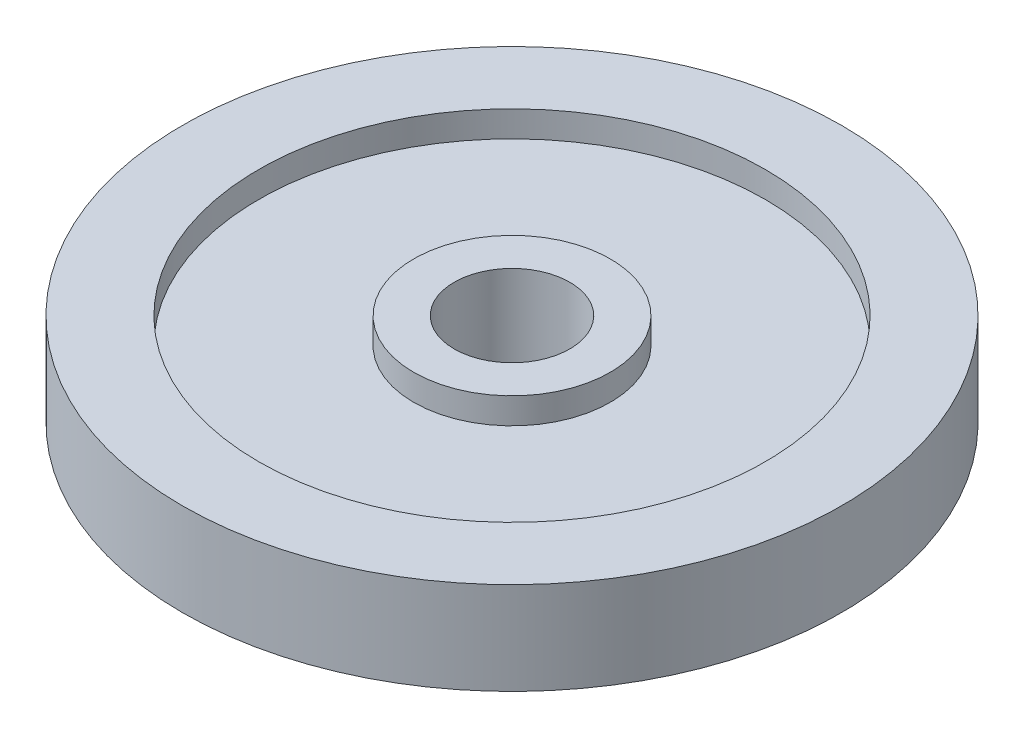
SolidWorks part; units mm, degrees
ref_plane "Front Plane" through (0, 0, 0) normal (0, 0, 1) x (1, 0, 0)
ref_plane "Top Plane" through (0, 0, 0) normal (0, 1, 0) x (1, 0, 0)
ref_plane "Right Plane" through (0, 0, 0) normal (1, 0, 0) x (0, 0, -1)
sketch "Sketch1" plane through (0, 0, 0) normal (0, 1, 0) x (1, 0, 0)
  circle A0 centre (0, 0) radius 36.195
  circle A1 centre (0, 0) radius 6.35
  dimension "D1" = 72.39
  dimension "D2" = 12.7
extrude "Disk" add sketch "Sketch1" along normal blind 10.16
sketch "Sketch2" plane through (0, 10.16, 0) normal (0, 1, 0) x (1, 0, 0)
  circle A0 centre (0, 0) radius 10.795
  circle A1 centre (0, 0) radius 27.813
  circle A2 centre (0, 0) radius 36.195 construction
  dimension "D1" = 21.59
  dimension "D2" = 8.382
extrude "Cut-Extrude1" cut sketch "Sketch2" against normal blind 2.8575
ref_plane "Plane1" through (0, 5.08, 0) normal (0, 1, 0) x (1, 0, 0)
mirror "Mirror1" about plane through (0, 5.08, 0) normal (0, 1, 0) of "Cut-Extrude1"
